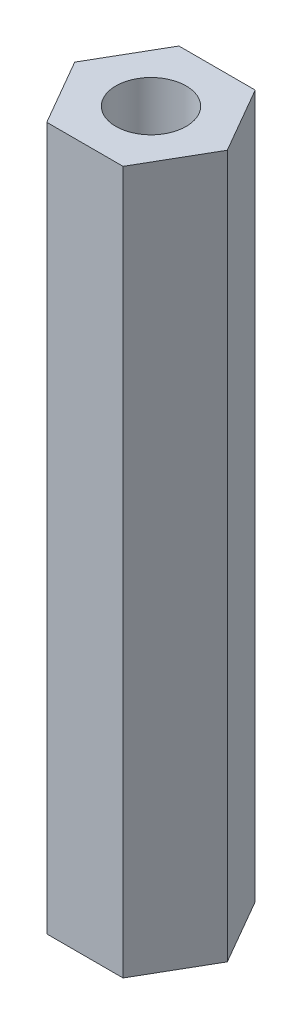
SolidWorks part; units mm, degrees
ref_plane "Front Plane" through (0, 0, 0) normal (0, 0, 1) x (1, 0, 0)
ref_plane "Top Plane" through (0, 0, 0) normal (0, 1, 0) x (1, 0, 0)
ref_plane "Right Plane" through (0, 0, 0) normal (1, 0, 0) x (0, 0, -1)
sketch "Sketch1" plane through (0, 0, 0) normal (0, 1, 0) x (1, 0, 0)
  line L1 (1.3568, 2.35) -> (-1.3568, 2.35)
  line L2 (-1.3568, 2.35) -> (-2.7135, 0)
  line L3 (-2.7135, 0) -> (-1.3568, -2.35)
  line L4 (-1.3568, -2.35) -> (1.3568, -2.35)
  line L5 (1.3568, -2.35) -> (2.7135, 0)
  line L6 (2.7135, 0) -> (1.3568, 2.35)
  circle A0 centre (0, 0) radius 2.35 construction
  circle A1 centre (0, 0) radius 1.25
  dimension "D2" = 2.5
  dimension "D1" = 4.7
extrude "Boss-Extrude1" add sketch "Sketch1" along normal blind 25
sketch "Sketch2" plane through (0, 0, 0) normal (0, 1, 0) x (1, 0, 0)
  circle A0 centre (0, 0) radius 1.25 construction
  circle A1 centre (0, 0) radius 1.25
